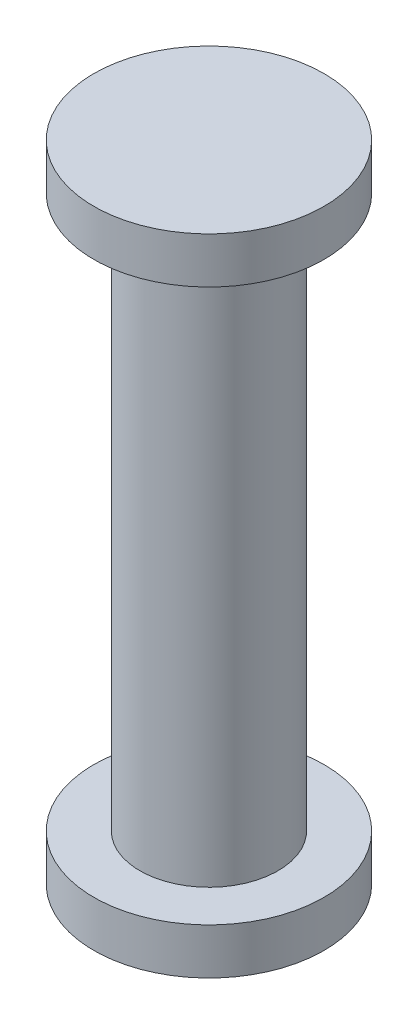
SolidWorks part; units mm, degrees
ref_plane "Front Plane" through (0, 0, 0) normal (0, 0, 1) x (1, 0, 0)
ref_plane "Top Plane" through (0, 0, 0) normal (0, 1, 0) x (1, 0, 0)
ref_plane "Right Plane" through (0, 0, 0) normal (1, 0, 0) x (0, 0, -1)
sketch "Sketch1" plane through (0, 0, 0) normal (0, 0, 1) x (1, 0, 0)
  line L0 (0, 0) -> (0, 14)
  line L1 (0, 14) -> (-2.0817, 14)
  line L2 (-1.5, 13) -> (-1.5, 1)
  line L3 (-1.5, 1) -> (-2.5, 1)
  line L4 (-2.5, 1) -> (-2.5, 0)
  line L5 (-2.5, 0) -> (0, 0)
  line L6 (-2.0817, 14) -> (-2.5, 14)
  line L7 (-2.5, 14) -> (-2.5, 13)
  line L8 (-2.5, 13) -> (-1.5, 13)
  dimension "D1" = 14
  dimension "D2" = 2.5
  dimension "D3" = 1
  dimension "D4" = 1.5
  dimension "D5" = 1
revolve "Revolve1" add sketch "Sketch1" angle 360 about L0
